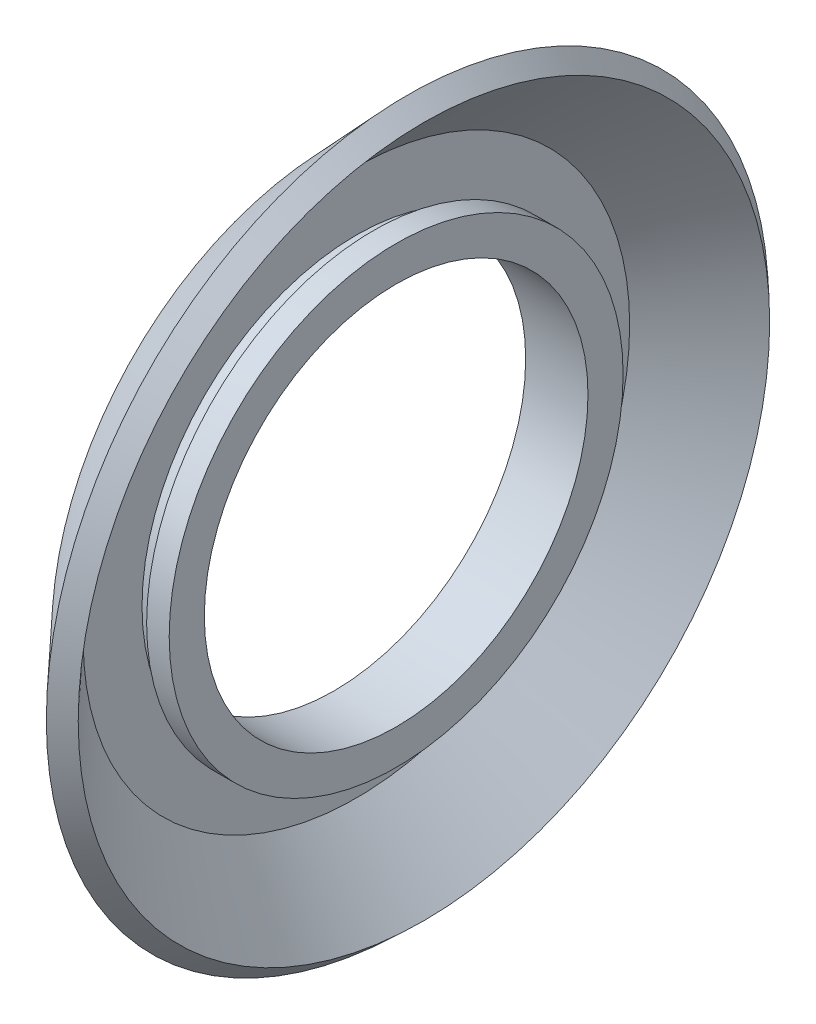
SolidWorks part; units mm, degrees
ref_plane "Plan de face" through (0, 0, 0) normal (0, 0, 1) x (1, 0, 0)
ref_plane "Plan de dessus" through (0, 0, 0) normal (0, 1, 0) x (1, 0, 0)
ref_plane "Plan de droite" through (0, 0, 0) normal (1, 0, 0) x (0, 0, -1)
sketch "Esquisse1" plane through (0, 0, 0) normal (0, 0, 1) x (1, 0, 0)
  line L0 (-7.8927, 0) -> (52.4862, 0) construction
  line L1 (0, 8.5) -> (0, 12.5)
  line L2 (0, 12.5) -> (3.26, 16)
  line L3 (0, 8.5) -> (2.76, 8.5)
  line L4 (2.76, 8.5) -> (2.76, 10.0563)
  dimension "D1" = 32
  dimension "D2" = 25
  dimension "D3" = 3.26
  dimension "D4" = 17
  dimension "D5" = 0.5
revolve "Révol.-Mince2" add sketch "Esquisse1" angle 360 about L0
